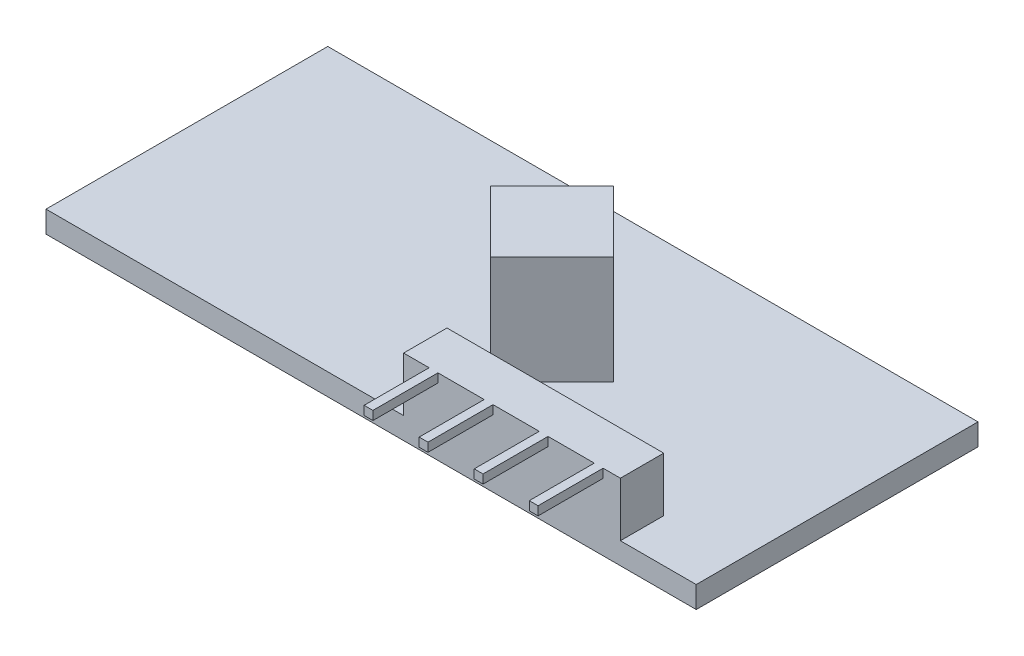
SolidWorks part; units mm, degrees
ref_plane "Front Plane" through (0, 0, 0) normal (0, 0, 1) x (1, 0, 0)
ref_plane "Top Plane" through (0, 0, 0) normal (0, 1, 0) x (1, 0, 0)
ref_plane "Right Plane" through (0, 0, 0) normal (1, 0, 0) x (0, 0, -1)
sketch "Sketch1" plane through (0, 0, 0) normal (0, 1, 0) x (1, 0, 0)
  line L1 (-15, -6.5) -> (15, -6.5)
  line L2 (-15, -6.5) -> (-15, 6.5)
  line L3 (-15, 6.5) -> (15, 6.5)
  line L4 (15, -6.5) -> (15, 6.5)
  line L5 (-15, -6.5) -> (15, 6.5) construction
  line L6 (-15, 6.5) -> (15, -6.5) construction
  point P0 (0, 0)
  dimension "D1" = 30
  dimension "D2" = 13
extrude "Boss-Extrude1" add sketch "Sketch1" along normal blind 1
sketch "Sketch2" plane through (0, 1, 0) normal (0, 1, 0) x (1, 0, 0)
  line L0 (-15, -6.5) -> (15, -6.5) construction
  line L1 (1.5, -4.5) -> (11.5, -4.5)
  line L2 (1.5, -4.5) -> (1.5, -6.5)
  line L3 (1.5, -6.5) -> (11.5, -6.5)
  line L4 (11.5, -4.5) -> (11.5, -6.5)
  line L5 (1.5, -4.5) -> (11.5, -6.5) construction
  line L6 (1.5, -6.5) -> (11.5, -4.5) construction
  line L7 (15, -6.5) -> (15, 6.5) construction
  point P0 (6.5, -5.5)
  dimension "D1" = 10
  dimension "D2" = 3.5
  dimension "D3" = 2
extrude "Boss-Extrude2" add sketch "Sketch2" along normal blind 2.5
sketch "Sketch4" plane through (0, 0, 6.5) normal (0, 0, 1) x (1, 0, 0)
  line L1 (1.5, 3.5) -> (11.5, 3.5) construction
  line L2 (11.5, 3.5) -> (11.5, 1) construction
  line L21 (10.2968, 3.0936) -> (10.7032, 3.0936)
  line L22 (10.2968, 3.0936) -> (10.2968, 3.5)
  line L23 (10.2968, 3.5) -> (10.7032, 3.5)
  line L24 (10.7032, 3.0936) -> (10.7032, 3.5)
  line L25 (10.2968, 3.0936) -> (10.7032, 3.5) construction
  line L26 (10.2968, 3.5) -> (10.7032, 3.0936) construction
  point P17 (10.5, 3.2968)
  dimension "D1" = 0.4064
  dimension "D2" = 1
extrude "Boss-Extrude3" add sketch "Sketch4" along normal blind 3
pattern_linear "LPattern1" count 4 spacing 2.54 along (-1, 0, 0) of "Boss-Extrude3"
sketch "Sketch5" plane through (0, 1, 0) normal (0, 1, 0) x (1, 0, 0)
  line L0 (-0.6569, -0.3284) -> (2.1716, -3.1569)
  line L1 (-0.6569, -0.3284) -> (2.1716, 2.5)
  line L2 (2.1716, -3.1569) -> (5, -0.3284)
  line L3 (2.1716, 2.5) -> (5, -0.3284)
  line L4 (-0.6569, -0.3284) -> (5, -0.3284) construction
  line L5 (2.1716, -3.1569) -> (2.1716, 2.5) construction
  line L6 (15, -6.5) -> (15, 6.5) construction
  line L7 (15, 6.5) -> (-15, 6.5) construction
  point P1 (2.1716, -0.3284)
  dimension "D1" = 4
  dimension "D2" = 10
  dimension "D3" = 4
extrude "Boss-Extrude4" add sketch "Sketch5" along normal blind 5
